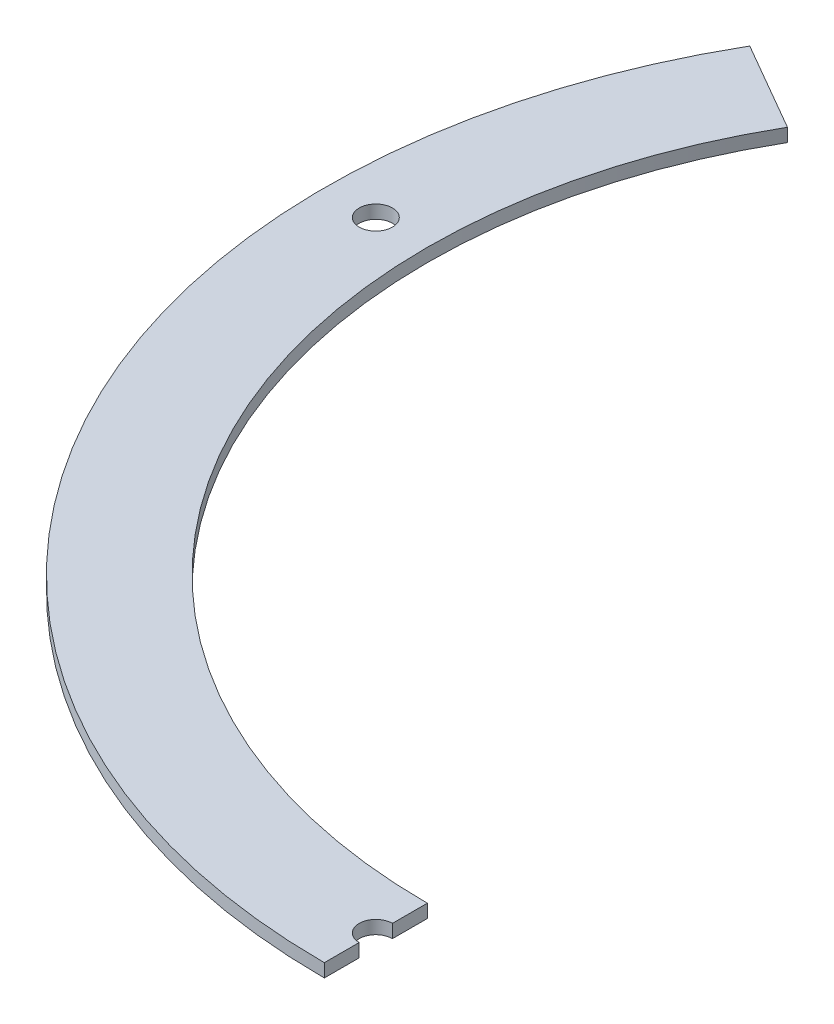
SolidWorks part; units mm, degrees
ref_plane "前视基准面" through (0, 0, 0) normal (0, 0, 1) x (1, 0, 0)
ref_plane "上视基准面" through (0, 0, 0) normal (0, 1, 0) x (1, 0, 0)
ref_plane "右视基准面" through (0, 0, 0) normal (1, 0, 0) x (0, 0, -1)
other "Configuration Table"
sketch "草图1" plane through (0, 0, 0) normal (0, 1, 0) x (1, 0, 0)
  line L0 (0, 0) -> (0, 101)
  line L1 (0, 85.5) -> (0, 72.5)
  line L2 (0, 85.5) -> (0, 101)
  circle A0 centre (0, 0) radius 72.5
  circle A1 centre (0, 0) radius 85.5
  circle A2 centre (0, 0) radius 101
  circle A3 centre (0, 79) radius 2.5
  circle A4 centre (79, 0) radius 2.5
  circle A5 centre (0, -79) radius 2.5
  circle A6 centre (-79, 0) radius 2.5
  circle A7 centre (0, 93.25) radius 2.5
  circle A8 centre (93.25, 0) radius 2.5
  circle A9 centre (0, -93.25) radius 2.5
  circle A10 centre (-93.25, 0) radius 2.5
  point P20 (0, 0)
  point P29 (0, 0)
  dimension "D1" = 145
  dimension "D3" = 202
  dimension "D4" = 5
  dimension "D5" = 5
  dimension "D2" = 13
extrude "凸台-拉伸2" add sketch "草图1" along normal blind 2
sketch "草图4" plane through (0, 0, 0) normal (0, -1, 0) x (1, 0, 0)
  line L0 (0, 0) -> (0, 101)
  line L1 (0, 0) -> (87.4686, -50.5)
  line L2 (0, 0) -> (-87.4686, -50.5)
  circle A0 centre (0, 0) radius 101 construction
  circle A1 centre (0, 0) radius 101
  point P9 (0, 0)
  circle M1 centre (0, -93.25) radius 2.5
  circle M2 centre (0, 0) radius 101
  circle M6 centre (0, 0) radius 85.5
extrude "切除-拉伸2" cut sketch "草图4" against normal blind 2 contours L2 L1 M6 M2 M1
sketch "草图5" plane through (0, 0, 0) normal (0, -1, 0) x (1, 0, 0)
  line L0 (0, 0) -> (0, 101)
  line L1 (0, 0) -> (87.4686, -50.5)
  arc A0 (87.4686, -50.5) -> (-87.4686, -50.5) centre (0, 0) ccw construction
  circle A1 centre (0, 0) radius 101
  circle M3 centre (93.25, 0) radius 2.5
  circle M4 centre (0, 93.25) radius 2.5
  line M6 (74.0452, -42.75) -> (87.4686, -50.5)
  arc M7 (87.4686, -50.5) -> (-87.4686, -50.5) centre (0, 0) ccw
  arc M9 (-74.0452, -42.75) -> (74.0452, -42.75) centre (0, 0) cw
extrude "切除-拉伸3" cut sketch "草图5" against normal blind 2 contours L0 M9 M6 M7 M4 M3
